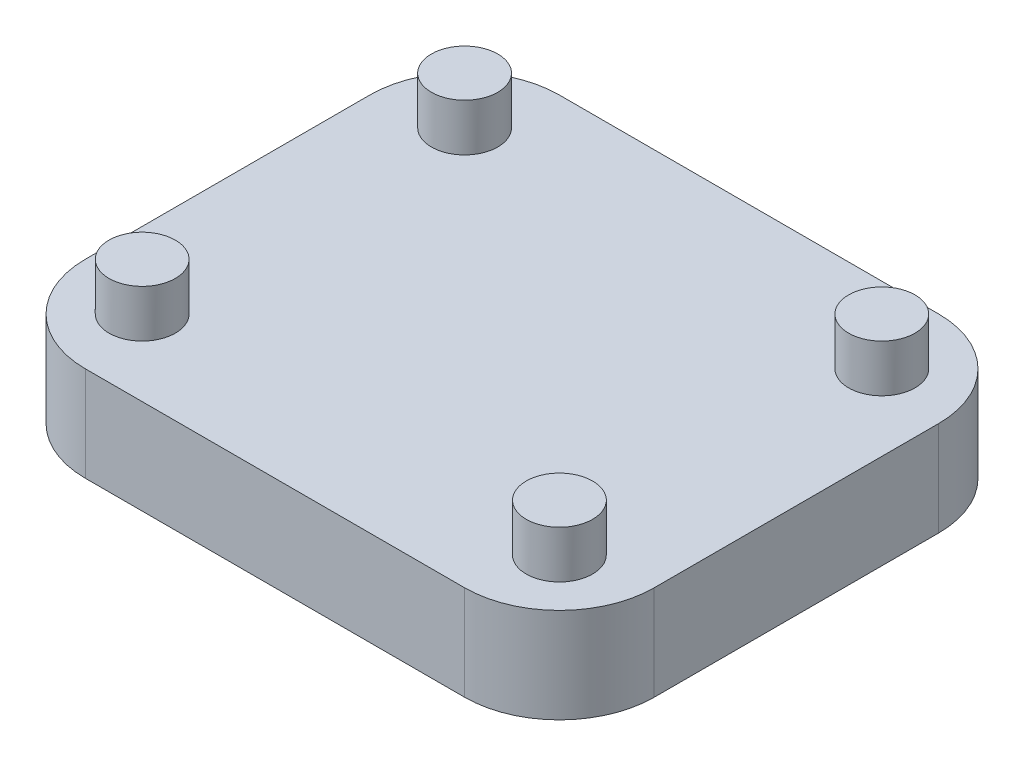
SolidWorks part; units mm, degrees
ref_plane "Front Plane" through (0, 0, 0) normal (0, 0, 1) x (1, 0, 0)
ref_plane "Top Plane" through (0, 0, 0) normal (0, 1, 0) x (1, 0, 0)
ref_plane "Right Plane" through (0, 0, 0) normal (1, 0, 0) x (0, 0, -1)
sketch "Sketch1" plane through (0, 0, 0) normal (0, 1, 0) x (1, 0, 0)
  line L1 (-2, 0) -> (-10, 0)
  line L2 (0, -2) -> (0, -8)
  line L3 (-2, -10) -> (-10, -10)
  line L4 (-12, -2) -> (-12, -8)
  arc A0 (-2, 0) -> (0, -2) centre (-2, -2) cw
  arc A1 (0, -8) -> (-2, -10) centre (-2, -8) cw
  arc A2 (-10, -10) -> (-12, -8) centre (-10, -8) cw
  arc A3 (-10, 0) -> (-12, -2) centre (-10, -2) ccw
  point P7 (0, 0)
  point P12 (-12, -10)
  point P15 (-12, 0)
  dimension "D3" = 2
  dimension "D1" = 12
  dimension "D2" = 10
extrude "Boss-Extrude1" add sketch "Sketch1" along normal blind 2
sketch "Sketch3" plane through (0, 2, 0) normal (0, 1, 0) x (1, 0, 0)
  line L0 (-12, -2) -> (-12, -8) construction
  line L1 (-2, 0) -> (-10, 0) construction
  line L2 (-10, -10) -> (-2, -10) construction
  line L3 (0, -8) -> (0, -2) construction
  circle A0 centre (-10.4, -1.6) radius 0.7
  circle A1 centre (-1.6, -1.6) radius 0.7
  circle A2 centre (-1.6, -8.4) radius 0.7
  circle A3 centre (-10.4, -8.4) radius 0.7
  point P14 (0, 0)
  dimension "D1" = 1.4
  dimension "D2" = 1.4
  dimension "D3" = 1.4
  dimension "D4" = 1.4
  dimension "D5" = 1.6
  dimension "D6" = 1.6
  dimension "D7" = 1.6
  dimension "D8" = 1.6
  dimension "D9" = 1.6
extrude "Boss-Extrude3" add sketch "Sketch3" along normal blind 1
